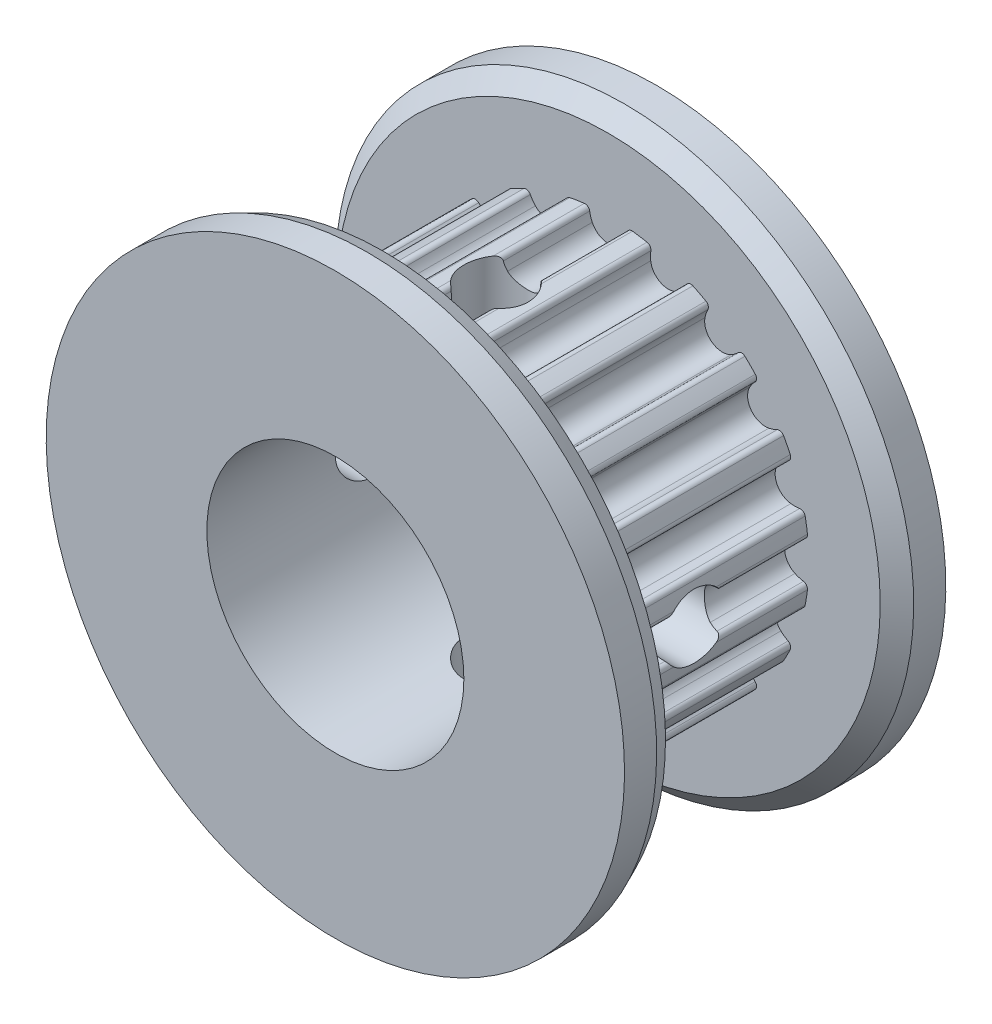
SolidWorks part; units mm, degrees
material "Aleación 6061"
ref_plane "Alzado" through (0, 0, 0) normal (0, 0, 1) x (1, 0, 0)
ref_plane "Planta" through (0, 0, 0) normal (0, 1, 0) x (1, 0, 0)
ref_plane "Vista lateral" through (0, 0, 0) normal (1, 0, 0) x (0, 0, -1)
sketch "Croquis1" plane through (0, 0, 0) normal (0, 0, 1) x (1, 0, 0)
  circle A0 centre (0, 0) radius 6.366
  dimension "D1" = 12.732
extrude "Saliente-Extruir1" add sketch "Croquis1" along normal blind 7
sketch "Croquis3" plane through (0, 0, 0) normal (0, 0, -1) x (-1, 0, 0)
  line L0 (0, 0) -> (0, 6.239) construction
  line L1 (0, 0) -> (0.976, 6.1622) construction
  line L2 (0.976, 6.1622) -> (0, 0) construction
  line L3 (0, 0) -> (-0.976, 6.1622) construction
  line L6 (0.976, 6.1622) -> (0.9959, 6.2876)
  line L8 (-0.976, 6.1622) -> (-0.9959, 6.2876)
  arc A0 (-0.7498, 6.1938) -> (-0.976, 6.1622) centre (0, 0) ccw
  arc A1 (-0.5037, 5.8059) -> (0.5037, 5.8059) centre (0, 6.039) ccw
  arc A2 (-0.5837, 6.0685) -> (-0.5037, 5.8059) centre (0.4038, 6.2259) ccw
  arc A3 (-0.5837, 6.0685) -> (-0.7498, 6.1938) centre (-0.7318, 6.0449) ccw
  arc A4 (0.5837, 6.0685) -> (0.5037, 5.8059) centre (-0.4038, 6.2259) cw
  arc A5 (0.5837, 6.0685) -> (0.7498, 6.1938) centre (0.7318, 6.0449) cw
  arc A6 (0.7498, 6.1938) -> (0.976, 6.1622) centre (0, 0) cw
  circle A7 centre (0, 0) radius 6.366 construction
  circle A11 centre (0, 0) radius 6.366
  circle M8 centre (0, 0) radius 6.366
  dimension "D1" = 6.239
  dimension "D4" = 1.11
  dimension "D5" = 2
  dimension "D7" = 0.3
  dimension "D3" = 18
  dimension "D6" = 0.2
extrude "Cortar-Extruir1" cut sketch "Croquis3" against normal through all contours A5 A6 L6 L8 A0 A3 A2 A1 A4 M8
pattern_circular "MatrizC1" count 20 over 360 about axis through (0, 0, 0) along (0, 0, 1) of "Cortar-Extruir1"
sketch "Croquis5" plane through (0, 0, 0) normal (1, 0, 0) x (0, 0, -1)
  line L0 (0, 0) -> (1.5, 0)
  line L1 (0, -0.5037) -> (0, 0.5037) construction
  line L2 (1.5, 0) -> (1.5, 9)
  line L4 (0, 8.4583) -> (0, 0)
  line L5 (-7, 0) -> (-8.5, 0)
  line L6 (-7, 0.5037) -> (-7, -0.5037) construction
  line L7 (-8.5, 0) -> (-8.5, 9)
  line L10 (-7, 0) -> (-7, 8.776)
  line L11 (-8.5, 9) -> (-7.5, 9)
  line L12 (-7.5, 9) -> (-7, 8.776)
  line L13 (1.5, 9) -> (0.5, 9)
  line L14 (0.5, 9) -> (0, 8.4583)
  dimension "D1" = 9
  dimension "D2" = 1
  dimension "D3" = 9
  dimension "D4" = 0.5
  dimension "D5" = 1
  dimension "D6" = 0.5
revolve "Revolución1" add sketch "Croquis5" angle 360 about L5
sketch "Croquis6" plane through (0, 0, 8.5) normal (0, 0, 1) x (1, 0, 0)
  circle A0 centre (0, 0) radius 4
  dimension "D1" = 8
extrude "Cortar-Extruir2" cut sketch "Croquis6" against normal through all
sketch "Croquis7" plane through (0, 0, 0) normal (1, 0, 0) x (0, 0, -1)
  circle A0 centre (-3.5, 0) radius 1
  dimension "D1" = 2
extrude "Cortar-Extruir3" cut sketch "Croquis7" against normal through all both and the other way through all
sketch "Croquis8" plane through (0, 0, 0) normal (0, 1, 0) x (1, 0, 0)
  line L0 (0, 1.5) -> (0, -8.5) construction
  line L1 (9, 1.5) -> (-9, 1.5) construction
  line L2 (-4, -8.5) -> (4, -8.5) construction
  circle A1 centre (0, -3.5) radius 1
  dimension "D1" = 2
extrude "Cortar-Extruir4" cut sketch "Croquis8" against normal through all both and the other way through all
